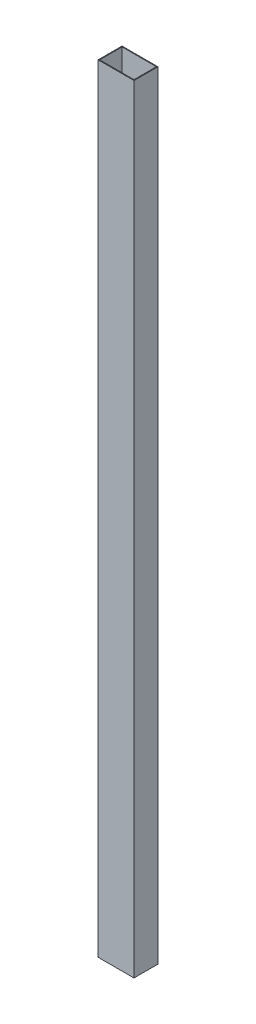
SolidWorks part; units mm, degrees
ref_plane "Front Plane" through (0, 0, 0) normal (0, 0, 1) x (1, 0, 0)
ref_plane "Top Plane" through (0, 0, 0) normal (0, 1, 0) x (1, 0, 0)
ref_plane "Right Plane" through (0, 0, 0) normal (1, 0, 0) x (0, 0, -1)
sketch "Sketch1" plane through (0, 0, 0) normal (0, 1, 0) x (1, 0, 0)
  line L1 (0, 0) -> (-76.2, 0)
  line L2 (0, 0) -> (0, 50.8)
  line L3 (0, 50.8) -> (-76.2, 50.8)
  line L4 (-76.2, 0) -> (-76.2, 50.8)
  line L5 (-74.6125, 1.5875) -> (-1.5875, 1.5875)
  line L6 (-74.6125, 1.5875) -> (-74.6125, 49.2125)
  line L7 (-74.6125, 49.2125) -> (-1.5875, 49.2125)
  line L8 (-1.5875, 1.5875) -> (-1.5875, 49.2125)
  dimension "D1" = 76.2
  dimension "D2" = 50.8
  dimension "D3" = 1.5875
  dimension "D4" = 1.5875
  dimension "D5" = 1.5875
  dimension "D6" = 1.5875
extrude "Boss-Extrude1" add sketch "Sketch1" along normal blind 1651
